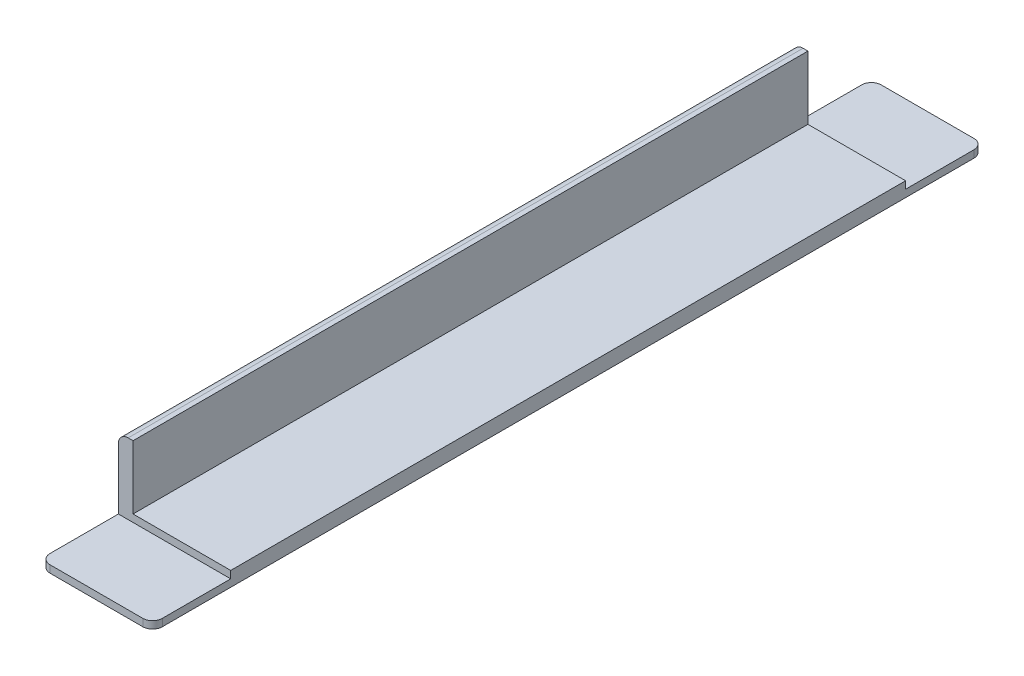
SolidWorks part; units mm, degrees
ref_plane "前视基准面" through (0, 0, 0) normal (0, 0, 1) x (1, 0, 0)
ref_plane "上视基准面" through (0, 0, 0) normal (0, 1, 0) x (1, 0, 0)
ref_plane "右视基准面" through (0, 0, 0) normal (1, 0, 0) x (0, 0, -1)
other "Configuration Table"
sketch "草图1" plane through (0, 0, 0) normal (0, 0, 1) x (1, 0, 0)
  line L0 (0, 0) -> (23, 0)
  line L1 (23, 0) -> (23, 3)
  line L2 (23, 3) -> (3, 3)
  line L3 (3, 3) -> (3, 16)
  line L4 (3, 16) -> (0, 16)
  line L5 (0, 16) -> (0, 0)
  dimension "D1" = 23
  dimension "D2" = 16
  dimension "D3" = 3
  dimension "D4" = 3
extrude "凸台-拉伸1" add sketch "草图1" along normal blind 138.2
fillet "圆角1" radius 2 1 edges at (0, 16, 69.1)
sketch "草图2" plane through (0, 0, 0) normal (0, -1, 0) x (1, 0, 0)
  line L0 (23, 138.2) -> (23, 0) construction
  line L1 (23, 138.2) -> (0, 138.2)
  line L2 (23, 138.2) -> (23, 154.2)
  line L3 (23, 154.2) -> (0, 154.2)
  line L4 (0, 138.2) -> (0, 154.2)
  line L5 (0, 0) -> (23, 0)
  line L6 (0, 0) -> (0, -16)
  line L7 (0, -16) -> (23, -16)
  line L8 (23, 0) -> (23, -16)
  dimension "D1" = 16
  dimension "D2" = 16
extrude "凸台-拉伸2" add sketch "草图2" against normal blind 1.5
fillet "圆角2" radius 2 4 edges at (23, 0.75, -16) (0, 0.75, -16) (0, 0.75, 154.2) (23, 0.75, 154.2)
sketch "草图3" plane through (0, 0, 0) normal (-1, 0, 0) x (0, 0, 1)
  text T0 "Designed  By James YasR" font "黑体" height 3.5
extrude "切除-拉伸1" cut sketch "草图3" against normal blind 0.5
